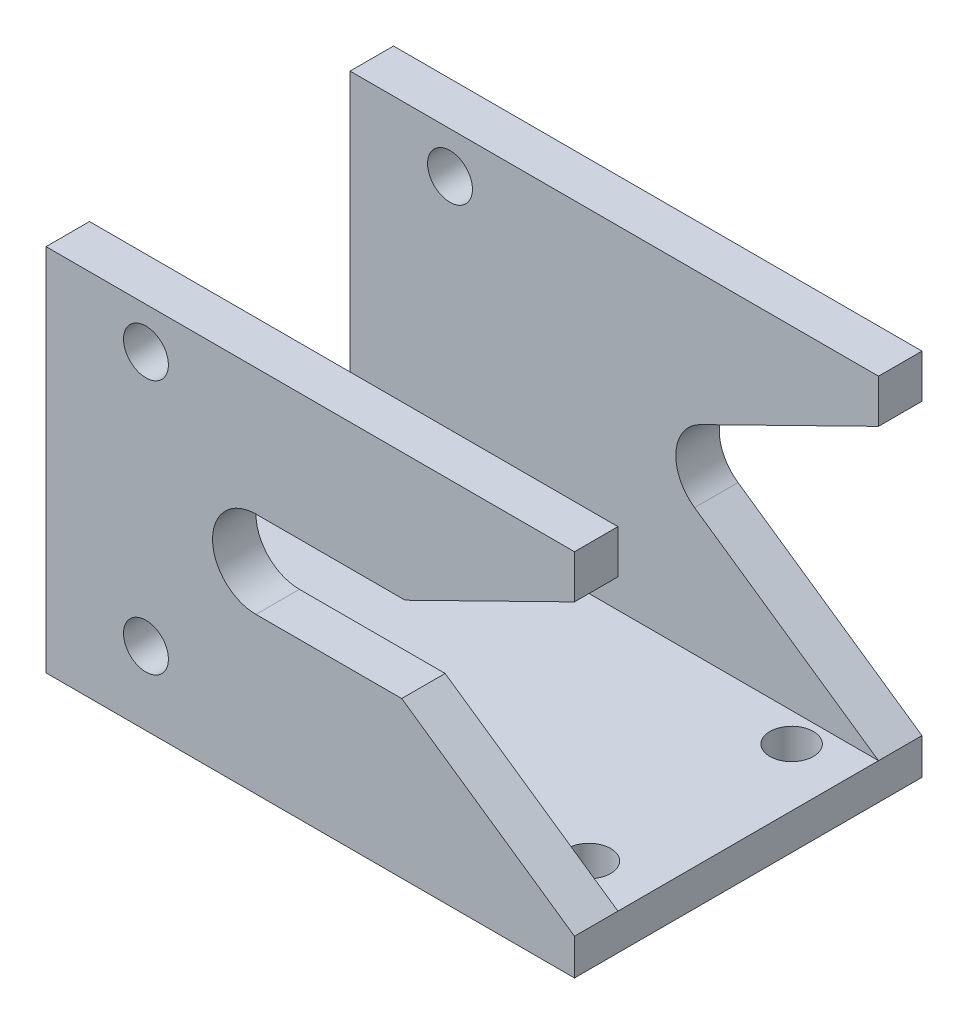
SolidWorks part; units mm, degrees
ref_plane "Front Plane" through (0, 0, 0) normal (0, 0, 1) x (1, 0, 0)
ref_plane "Top Plane" through (0, 0, 0) normal (0, 1, 0) x (1, 0, 0)
ref_plane "Right Plane" through (0, 0, 0) normal (1, 0, 0) x (0, 0, -1)
sketch "Sketch1" plane through (0, 0, 0) normal (0, 1, 0) x (1, 0, 0)
  line L1 (0, 0) -> (36.5, 0)
  line L2 (0, 0) -> (0, 24)
  line L3 (0, 24) -> (36.5, 24)
  line L4 (36.5, 0) -> (36.5, 24)
  dimension "D1" = 36.5
  dimension "D2" = 24
extrude "Boss-Extrude1" add sketch "Sketch1" along normal blind 2.5
sketch "Sketch2" plane through (0, 2.5, 0) normal (0, 1, 0) x (1, 0, 0)
  line L0 (0, 24) -> (0, 0) construction
  line L1 (0, 3) -> (36.5, 3)
  line L2 (0, 3) -> (0, 0)
  line L3 (0, 0) -> (36.5, 0)
  line L4 (36.5, 3) -> (36.5, 0)
  line L5 (36.5, 0) -> (36.5, 24) construction
  line L6 (36.5, 21) -> (0, 21)
  line L7 (36.5, 21) -> (36.5, 24)
  line L8 (36.5, 24) -> (0, 24)
  line L9 (0, 21) -> (0, 24)
  dimension "D1" = 3
  dimension "D2" = 3
extrude "Boss-Extrude2" add sketch "Sketch2" along normal blind 23
sketch "Sketch3" plane through (0, 0, 0) normal (0, 0, 1) x (1, 0, 0)
  line L0 (36.5, 25.5) -> (36.5, 0) construction
  line L1 (36.5, 25.5) -> (36.5, 0)
  line L2 (23.7942, 11.2821) -> (36.5, 2.5)
  line L3 (0, 0) -> (36.5, 0) construction
  line L4 (36.5, 22.4972) -> (24.1771, 16.4426)
  circle A0 centre (25.5, 13.75) radius 3
  circle A1 centre (6.9, 5.05) radius 1.55
  circle A2 centre (6.9, 22.65) radius 1.55
  dimension "D1" = 6
  dimension "D2" = 11
  dimension "D3" = 13.75
  dimension "D4" = 2.5
  dimension "D7" = 3.1
  dimension "D8" = 5.05
  dimension "D9" = 17.6
  dimension "D10" = 29.6
  dimension "D11" = 29.6
  dimension "D12" = 3.1
  dimension "D5" = 15.4455
  dimension "D6" = 13.73
extrude "Cut-Extrude2" cut sketch "Sketch3" against normal through all contours A0 | A0 L2 L1 L4 | A2 | A1
sketch "Sketch5" plane through (0, 0, 0) normal (0, 0, 1) x (1, 0, 0)
  line L0 (36.5, 25.5) -> (36.5, 22.4972) construction
  line L1 (0, 0) -> (36.5, 0) construction
  line L2 (14.5, 10.75) -> (24.5641, 10.75)
  line L3 (23.7942, 11.2821) -> (36.5, 2.5) construction
  line L4 (14.5, 16.75) -> (24.8028, 16.75)
  line L5 (36.5, 22.4972) -> (24.1771, 16.4426) construction
  circle A0 centre (14.5, 13.75) radius 3
  dimension "D1" = 22
  dimension "D2" = 6
  dimension "D3" = 13.75
extrude "Cut-Extrude3" cut sketch "Sketch5" against normal up to next
sketch "Sketch6" plane through (0, 2.5, 0) normal (0, 1, 0) x (1, 0, 0)
  line L0 (18.25, 24) -> (18.25, 0) construction
  line L1 (36.5, 24) -> (0, 24) construction
  line L2 (0, 0) -> (36.5, 0) construction
  line L3 (0, 12) -> (36.5, 12) construction
  line L4 (0, 21) -> (0, 3) construction
  line L5 (36.5, 3) -> (36.5, 21) construction
  circle A0 centre (4, 19) radius 1.5
  circle A1 centre (32.5, 19) radius 1.5
  circle A2 centre (32.5, 5) radius 1.5
  circle A3 centre (4, 5) radius 1.5
  dimension "D1" = 3
  dimension "D2" = 4
  dimension "D3" = 5
extrude "Cut-Extrude4" cut sketch "Sketch6" against normal through all
